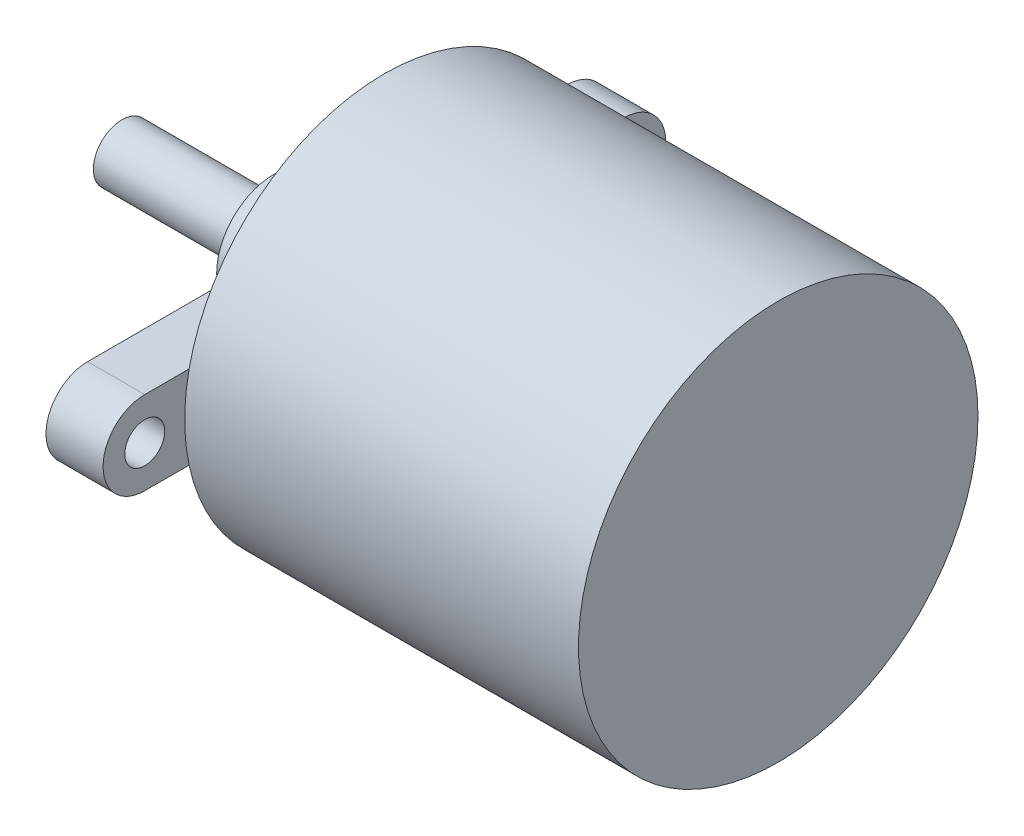
SolidWorks part; units mm, degrees
material "ABS"
ref_plane "Front" through (0, 0, 0) normal (0, 0, 1) x (1, 0, 0)
ref_plane "Top" through (0, 0, 0) normal (0, 1, 0) x (1, 0, 0)
ref_plane "Right" through (0, 0, 0) normal (1, 0, 0) x (0, 0, -1)
sketch "Sketch1" plane through (0, 0, 0) normal (1, 0, 0) x (0, 0, -1)
  circle A0 centre (0, 0) radius 17.5
  dimension "D1" = 35
extrude "Boss-Extrude1" add sketch "Sketch1" along normal blind 34.5
sketch "Sketch2" plane through (0, 0, 0) normal (-1, 0, 0) x (0, 0, 1)
  line L0 (-21, 0) -> (21, 0) construction
  line L1 (-21, 3.65) -> (21, 3.65)
  line L2 (-21, -3.65) -> (21, -3.65)
  arc A0 (-21, 3.65) -> (-21, -3.65) centre (-21, 0) ccw
  arc A1 (21, -3.65) -> (21, 3.65) centre (21, 0) ccw
  point P2 (0, 0)
  dimension "D1" = 3.65
  dimension "D2" = 42
extrude "Boss-Extrude2" add sketch "Sketch2" along normal blind 5
hole_wizard "Ø3.5 (3.5) Diameter Hole1" positions "Sketch4" profile "Sketch3" hole size "Ø3.5" standard "ANSI Metric"
sketch "Sketch4" plane through (-5, 0, 0) normal (-1, 0, 0) x (0, 0, 1)
  arc A0 (-21, 3.65) -> (-21, -3.65) centre (-21, 0) ccw construction
  arc A1 (21, -3.65) -> (21, 3.65) centre (21, 0) ccw construction
  point P0 (-21, -0.1403)
  point P1 (21, 0)
  dimension "D1" = 0
  dimension "D2" = 0
sketch "Sketch3" plane through (-5, -0.1403, -21) normal (0, 1, 0) x (0, 0, 1)
  line L0 (0, 0) -> (0, 71.0515)
  line L1 (0, 71.0515) -> (1.75, 70)
  line L2 (1.75, 70) -> (1.75, 0)
  line L5 (1.75, 0) -> (0, 0)
  line L10 (0, 71.0515) -> (-1.75, 70) construction
  line L11 (0, -6.35) -> (0, 107.95) construction
  dimension "Hole Dia." = 3.5
  dimension "Hole Depth" = 70
  dimension "Drill Angle" = 118
sketch "Sketch5" plane through (-5, 0, 0) normal (-1, 0, 0) x (0, 0, 1)
  circle A0 centre (0, 0) radius 5
  dimension "D1" = 10
extrude "Boss-Extrude3" add sketch "Sketch5" along normal blind 4.7
sketch "Sketch6" plane through (-9.7, 0, 0) normal (-1, 0, 0) x (0, 0, 1)
  circle A0 centre (0, 0) radius 2.5
  dimension "D1" = 5
extrude "Boss-Extrude4" add sketch "Sketch6" along normal blind 13.3
